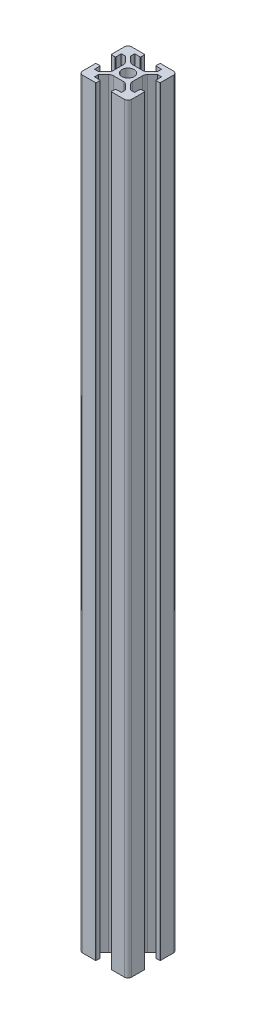
SolidWorks part; units mm, degrees
ref_plane "Front Plane" through (0, 0, 0) normal (0, 0, 1) x (1, 0, 0)
ref_plane "Top Plane" through (0, 0, 0) normal (0, 1, 0) x (1, 0, 0)
ref_plane "Right Plane" through (0, 0, 0) normal (1, 0, 0) x (0, 0, -1)
sketch "Sketch1" plane through (0, 0, 0) normal (0, 1, 0) x (1, 0, 0)
  line L0 (10, 20) -> (10, 10) construction
  line L1 (0, 0) -> (20, 0)
  line L2 (0, 0) -> (0, 20)
  line L3 (0, 20) -> (20, 20)
  line L4 (20, 0) -> (20, 20)
  line L5 (6.1, 13.9) -> (13.9, 13.9)
  line L6 (6.1, 13.9) -> (6.1, 6.1)
  line L7 (6.1, 6.1) -> (13.9, 6.1)
  line L8 (13.9, 13.9) -> (13.9, 6.1)
  line L9 (10, 10) -> (0, 10) construction
  line L10 (2.8607, 18.2) -> (18.2, 2.8607)
  line L11 (1.8, 18.2) -> (18.2, 18.2)
  line L12 (1.8, 18.2) -> (1.8, 1.8)
  line L13 (1.8, 1.8) -> (18.2, 1.8)
  line L14 (18.2, 18.2) -> (18.2, 1.8)
  line L15 (1.8, 17.1393) -> (17.1393, 1.8)
  line L16 (17.1393, 18.2) -> (1.8, 2.8607)
  line L17 (18.2, 17.1393) -> (2.8607, 1.8)
  line L18 (1.8, 18.2) -> (18.2, 1.8) construction
  line L19 (1.8, 17.1393) -> (2.3303, 17.6697) construction
  line L20 (2.3303, 17.6697) -> (2.8607, 18.2) construction
  line L21 (1.8, 1.8) -> (18.2, 18.2) construction
  line L22 (18.2, 1.8) -> (15.5, 1.8)
  line L23 (18.2, 1.8) -> (18.2, 4.5)
  line L24 (18.2, 4.5) -> (15.5, 4.5)
  line L25 (15.5, 1.8) -> (15.5, 4.5)
  line L26 (18.2, 13.1) -> (20, 13.1)
  line L27 (18.2, 18.2) -> (15.5, 18.2)
  line L28 (18.2, 18.2) -> (18.2, 15.5)
  line L29 (18.2, 15.5) -> (15.5, 15.5)
  line L30 (15.5, 18.2) -> (15.5, 15.5)
  line L31 (18.2, 6.9) -> (20, 6.9)
  line L32 (4.5, 18.2) -> (4.5, 15.5)
  line L33 (1.8, 15.5) -> (4.5, 15.5)
  line L34 (4.5, 1.8) -> (4.5, 4.5)
  line L35 (1.8, 4.5) -> (4.5, 4.5)
  line L36 (1.8, 6.9) -> (0, 6.9)
  line L37 (1.8, 13.1) -> (0, 13.1)
  line L38 (6.9, 20) -> (6.9, 18.2)
  line L39 (13.1, 20) -> (13.1, 18.2)
  line L40 (6.9, 0) -> (6.9, 1.8)
  line L41 (13.1, 0) -> (13.1, 1.8)
  circle A0 centre (10, 10) radius 2.5
  point P9 (10, 20)
  point P10 (10, 13.9)
  point P11 (0, 10)
  point P12 (6.1, 10)
  point P21 (10, 18.2)
  point P22 (1.8, 10)
  dimension "D3" = 5
  dimension "D1" = 20
  dimension "D2" = 6.1
  dimension "D4" = 1.5
  dimension "D5" = 1.5
  dimension "D6" = 1.8
  dimension "D7" = 11
  dimension "D8" = 6.2
  dimension "D9" = 6.9
  dimension "D10" = 6.2
  dimension "D11" = 6.9
extrude "Boss-Extrude1" add sketch "Sketch1" along normal blind 310 contours L38 L3 L2 L37 L12 L11 | L15 L33 L32 L10 L11 L12 | L32 L11 L10 | L12 L33 L15 | L33 L15 L6 L5 L10 L32 | L3 L39 L11 L14 L26 L4 | L11 L30 L16 | L16 L30 L29 L17 L14 L11 | L29 L14 L17 | L30 L16 L5 L8 L17 L29 | A0 L16 L5 L10 | A0 L10 L5 L6 L15 | A0 L17 L8 L5 L16 | A0 L10 L8 L17 | A0 L15 L6 L16 | A0 L16 L6 L7 L17 | A0 L17 L7 L15 | A0 L15 L7 L8 L10 | L16 L35 L34 L17 L7 L6 | L15 L25 L24 L10 L8 L7 | L35 L12 L16 | L35 L16 L12 L13 L17 L34 | L13 L34 L17 | L1 L40 L13 L12 L36 L2 | L14 L24 L10 | L25 L15 L13 L14 L10 L24 | L25 L13 L15 | L41 L1 L4 L31 L14 L13
fillet "Fillet1" radius 1.5 4 edges at (0, 155, -20) (0, 155, 0) (20, 155, -20) (20, 155, 0)
fillet "Fillet2" radius 0.2 32 edges at (20, 155, -13.1) (6.9, 155, -18.2) (0, 155, -13.1) (13.1, 155, -18.2) (18.2, 155, -13.1) (13.1, 155, 0) (13.1, 155, -1.8) (6.9, 155, 0) (6.9, 155, -1.8) (0, 155, -6.9) (1.8, 155, -6.9) (1.8, 155, -13.1) (6.9, 155, -20) (13.1, 155, -20) (18.2, 155, -6.9) (20, 155, -6.9) (4.5, 155, -3.4393) (15.5, 155, -3.4393) (18.2, 155, -4.5) (16.5607, 155, -4.5) (18.2, 155, -15.5) (16.5607, 155, -15.5) (15.5, 155, -16.5607) (15.5, 155, -18.2) (4.5, 155, -16.5607) (4.5, 155, -18.2) (3.4393, 155, -15.5) (1.8, 155, -15.5) (3.4393, 155, -4.5) (1.8, 155, -4.5) (15.5, 155, -1.8) (4.5, 155, -1.8)
fillet "Fillet3" radius 2 8 edges at (13.9, 155, -7.1607) (12.8393, 155, -6.1) (7.1607, 155, -6.1) (6.1, 155, -12.8393) (6.1, 155, -7.1607) (12.8393, 155, -13.9) (7.1607, 155, -13.9) (13.9, 155, -12.8393)
sketch "Sketch2" plane through (0, 0, -20) normal (0, 0, -1) x (-1, 0, 0)
  line L0 (-10, 310) -> (-10, 0) construction
  line L1 (-7.9891, 310) -> (-12.0109, 310) construction
  line L2 (-7.9891, 0) -> (-12.0109, 0) construction
  line L3 (-1.5, 0) -> (-6.7, 0) construction
  circle A0 centre (-10, 297) radius 2.1
  circle A1 centre (-10, 254) radius 2.1
  circle A2 centre (-10, 53) radius 2.1
  circle A3 centre (-10, 10) radius 2.1
  dimension "D3" = 4.2
  dimension "D1" = 43
  dimension "D2" = 254
  dimension "D4" = 10
  dimension "D5" = 43
extrude "Cut-Extrude1" cut sketch "Sketch2" against normal through all
